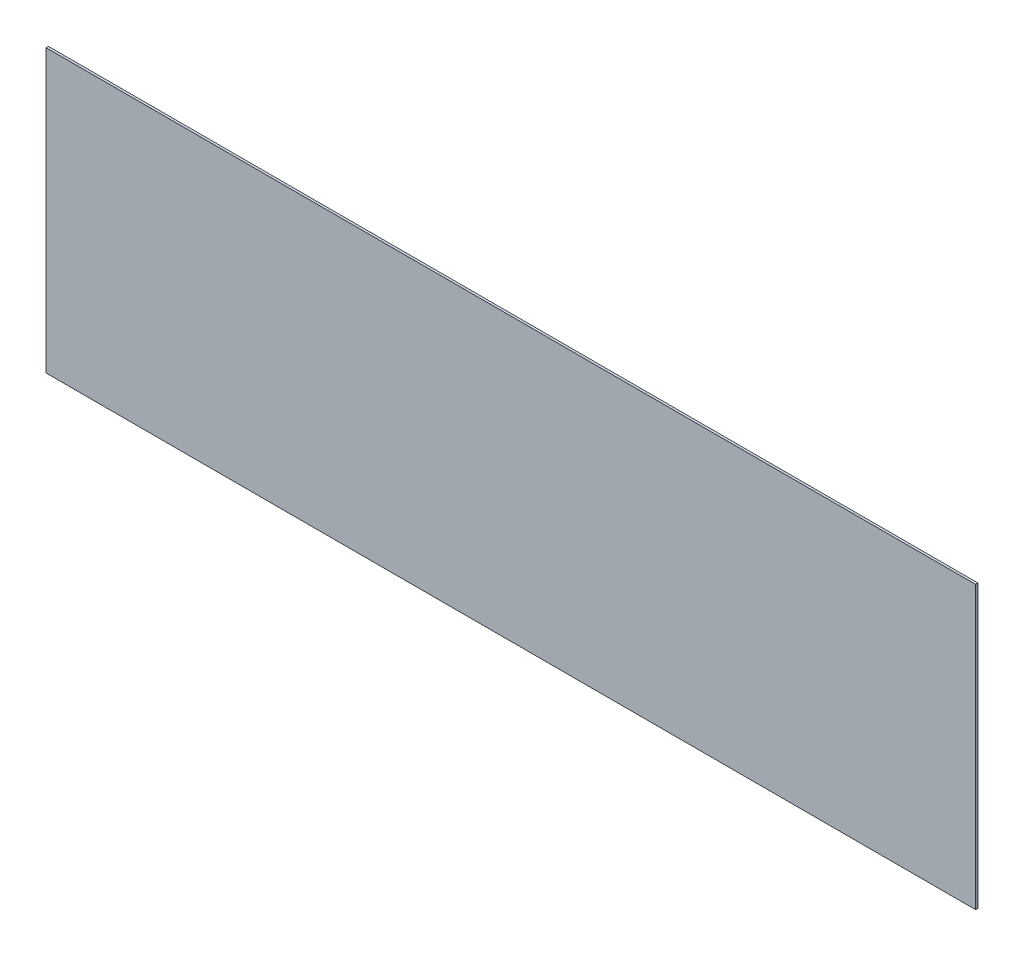
SolidWorks part; units mm, degrees
ref_plane "Front Plane" through (0, 0, 0) normal (0, 0, 1) x (1, 0, 0)
ref_plane "Top Plane" through (0, 0, 0) normal (0, 1, 0) x (1, 0, 0)
ref_plane "Right Plane" through (0, 0, 0) normal (1, 0, 0) x (0, 0, -1)
sketch "Sketch1" plane through (0, 0, 0) normal (0, 0, 1) x (1, 0, 0)
  line L1 (468.7566, -135.9526) -> (-116.6434, -135.9526)
  line L2 (468.7566, -135.9526) -> (468.7566, 41.4474)
  line L3 (468.7566, 41.4474) -> (-116.6434, 41.4474)
  line L4 (-116.6434, -135.9526) -> (-116.6434, 41.4474)
  line L5 (468.7566, -135.9526) -> (-116.6434, 41.4474) construction
  line L6 (468.7566, 41.4474) -> (-116.6434, -135.9526) construction
  point P0 (176.0566, -47.2526)
extrude "Boss-Extrude1" add sketch "Sketch1" along normal blind 1.5
